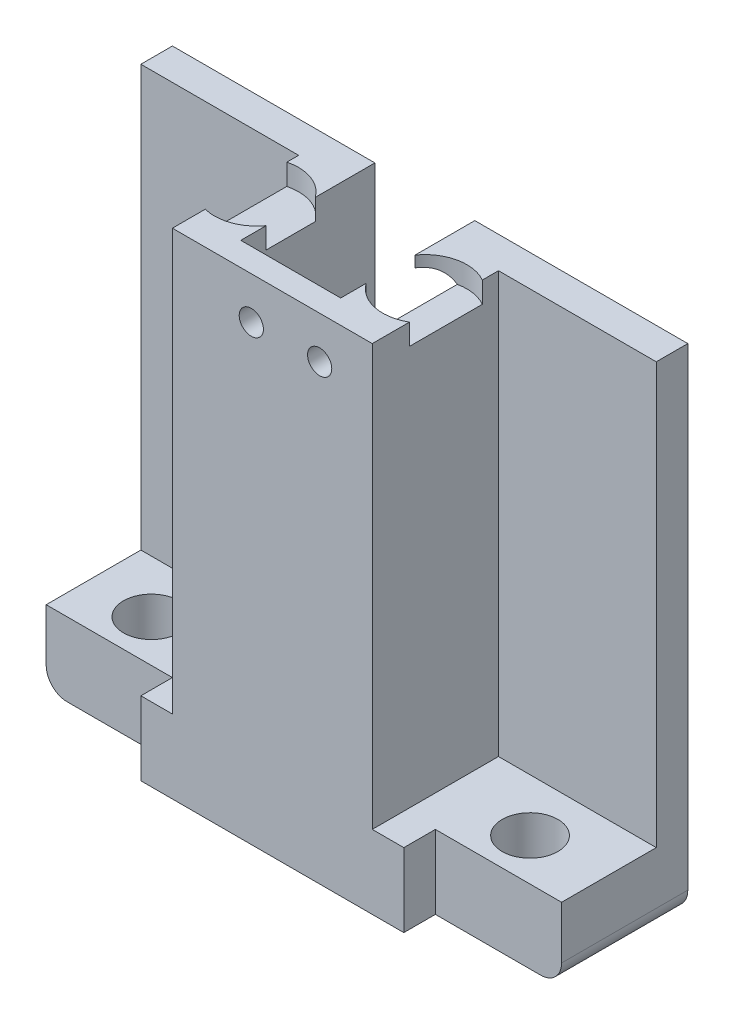
SolidWorks part; units mm, degrees
material "PLA"
ref_plane "前视基准面" through (0, 0, 0) normal (0, 0, 1) x (1, 0, 0)
ref_plane "上视基准面" through (0, 0, 0) normal (0, 1, 0) x (1, 0, 0)
ref_plane "右视基准面" through (0, 0, 0) normal (1, 0, 0) x (0, 0, -1)
other "Configuration Table"
sketch "草图1" plane through (0, 0, 0) normal (0, 0, 1) x (1, 0, 0)
  line L1 (-55, 53) -> (0, 53)
  line L2 (-55, 53) -> (-55, 0)
  line L3 (-55, 0) -> (0, 0)
  line L4 (0, 53) -> (0, 0)
  circle A2 centre (-52.5, 48) radius 1.15 construction
  circle A3 centre (-52.5, 41.5) radius 1.15 construction
  dimension "D2" = 53
  dimension "D4" = 2.5
  dimension "D7" = 2.3
  dimension "D8" = 6.5
  dimension "D9" = 5
  dimension "D10" = 52.5
  dimension "D3" = 55
extrude "凸台-拉伸1" add sketch "草图1" along normal blind 16
sketch "草图3" plane through (0, 0, 0) normal (0, -1, 0) x (1, 0, 0)
  line L0 (-55, 0) -> (0, 0) construction
  line L1 (0, 16) -> (0, 0) construction
  circle A0 centre (-43, 8) radius 2.65
  circle A1 centre (-7, 8) radius 2.65
  dimension "D1" = 36
  dimension "D2" = 5.3
  dimension "D3" = 8
  dimension "D4" = 7
extrude "切除-拉伸2" cut sketch "草图3" against normal through all
sketch "草图4" plane through (0, 0, 0) normal (0, -1, 0) x (1, 0, 0)
  line L0 (-29.75, 12.75) -> (-29.75, 0)
  line L2 (-29.75, 0) -> (-20.25, 0)
  line L3 (-20.25, 0) -> (-20.25, 12.75)
  line L4 (-25, 8) -> (-25, 23.0019) construction
  line L5 (-20.25, 12.75) -> (-29.75, 12.75)
  line L6 (-55, 0) -> (0, 0) construction
  line L7 (-7, 8) -> (-43, 8) construction
  circle A0 centre (-25, 8) radius 4.75 construction
  circle A1 centre (-7, 8) radius 2.65 construction
  circle A2 centre (-7, 8) radius 2.65 construction
  dimension "D1" = 9.5
  dimension "D2" = 9.5
extrude "切除-拉伸3" cut sketch "草图4" against normal through all
sketch "草图2" plane through (0, 0, 16) normal (0, 0, 1) x (1, 0, 0)
  line L0 (-37, 53) -> (-37, 0)
  line L1 (-12, 53) -> (-12, 0)
  line L2 (-37, 53) -> (-49, 53)
  line L3 (0, 53) -> (-55, 53) construction
  line L4 (0, 0) -> (0, 53)
  line L5 (0, 53) -> (-55, 53)
  line L6 (-55, 53) -> (-55, 0)
  line L7 (-55, 0) -> (0, 0)
  line L8 (0, 0) -> (0, 53)
  line L9 (0, 53) -> (-12, 53)
  line L12 (-49, 53) -> (-49, 0)
  line L13 (-49, 0) -> (-37, 0)
  line L14 (-49, 0) -> (-37, 0)
  line L15 (-12, 0) -> (0, 0)
  line M12 (0, 0) -> (0, 53)
  line M14 (0, 53) -> (-55, 53)
  line M31 (-55, 0) -> (0, 0)
  dimension "D2" = 37
  dimension "D3" = 12
  dimension "D4" = 12
  dimension "D1" = 0
extrude "切除-拉伸4" cut sketch "草图2" against normal blind 4 contours L12 L0 M14 M31 | L1 M14 M31 M12
sketch "草图5" plane through (0, 0, 12) normal (0, 0, 1) x (1, 0, 0)
  line L0 (-37, 53) -> (-37, 0) construction
  line L1 (-49, 53) -> (-37, 53)
  line L2 (-49, 53) -> (-49, 7)
  line L3 (-49, 7) -> (-37, 7)
  line L4 (-37, 53) -> (-37, 7)
  line L5 (0, 0) -> (0, 53) construction
  line L6 (-12, 53) -> (0, 53)
  line L7 (-12, 53) -> (-12, 7)
  line L8 (-12, 7) -> (0, 7)
  line L9 (0, 53) -> (0, 7)
  line L10 (-12, 53) -> (-12, 0) construction
  dimension "D1" = 46
extrude "切除-拉伸5" cut sketch "草图5" against normal blind 9
fillet "圆角1" radius 2 4 edges at (0, 53, 1.5) (-55, 53, 8) (0, 0, 6) (-55, 0, 8)
sketch "草图6" plane through (0, 0, 16) normal (0, 0, 1) x (1, 0, 0)
  line L0 (-49, 0) -> (-49, 53)
  line L1 (-53, 0) -> (-49, 0) construction
  line L2 (-49, 53) -> (-53, 53) construction
  line L3 (-53, 53) -> (-49, 53)
  line L4 (-49, 53) -> (-53, 53)
  line L5 (-55, 51) -> (-55, 2)
  line L6 (-53, 0) -> (-49, 0)
  line L7 (-49, 0) -> (-49, 53)
  line L9 (-55, 51) -> (-55, 2)
  line L12 (-49, 0) -> (-53, 0)
  line L13 (-37, 53) -> (-37, 0) construction
  arc A2 (-53, 53) -> (-55, 51) centre (-53, 51) ccw
  arc A3 (-55, 2) -> (-53, 0) centre (-53, 2) ccw
  arc A4 (-53, 53) -> (-55, 51) centre (-53, 51) ccw
  arc A5 (-55, 2) -> (-53, 0) centre (-53, 2) ccw
  dimension "D2" = 12
  dimension "D1" = 0
extrude "切除-拉伸6" cut sketch "草图6" against normal through all
fillet "圆角2" radius 2 2 edges at (-49, 53, 1.5) (-49, 0, 6)
sketch "草图12" plane through (0, 53, 0) normal (0, 1, 0) x (1, 0, 0)
  line L1 (-53.802, 11.0463) -> (2.1431, 11.0463)
  line L2 (-53.802, 11.0463) -> (-53.802, -22.1626)
  line L3 (-53.802, -22.1626) -> (2.1431, -22.1626)
  line L4 (2.1431, 11.0463) -> (2.1431, -22.1626)
  point P4 (2.1431, -22.1626)
extrude "切除-拉伸10" cut sketch "草图12" against normal blind 6
sketch "草图13" plane through (0, 0, 16) normal (0, 0, 1) x (1, 0, 0)
  line L0 (-12, 47) -> (-37, 47) construction
  line L1 (-49, 47) -> (-49, 7) construction
  circle A0 centre (-26.5, 43) radius 1.15
  circle A1 centre (-20, 43) radius 1.15
  point P8 (0, 0)
  dimension "D1" = 2.3
  dimension "D2" = 6.5
  dimension "D3" = 4
  dimension "D4" = 29
extrude "切除-拉伸11" cut sketch "草图13" against normal through all
sketch "草图8" [suppressed] plane through (0, 53, 0) normal (0, 1, 0) x (1, 0, 0)
  line L0 (-12, -16) -> (-37, -16) construction
  line L1 (-37, -16) -> (-27.65, -16)
  line L2 (-37, -16) -> (-37, -29)
  line L3 (-37, -29) -> (-27.65, -29)
  line L4 (-27.65, -16) -> (-27.65, -29)
  line L5 (-24.5, -16) -> (-24.5, -34.5504) construction
  line L6 (-21.35, -16) -> (-21.35, -29)
  line L7 (-12, -29) -> (-21.35, -29)
  line L8 (-12, -16) -> (-12, -29)
  line L9 (-12, -16) -> (-21.35, -16)
  dimension "D1" = 6.3
  dimension "D2" = 13
extrude "凸台-拉伸2" [suppressed] add sketch "草图8" against normal blind 6
sketch "草图9" [suppressed] plane through (-12, 0, 0) normal (1, 0, 0) x (0, 0, -1)
  line L0 (-16, 37) -> (-16, 0) construction
  line L1 (-29, 40) -> (-37.2325, 40) construction
  line L2 (-29, 37) -> (-29, 43) construction
  circle A0 centre (-16, 40) radius 1.15
  circle A1 centre (-22.5, 40) radius 1.15
  dimension "D1" = 2.3
  dimension "D2" = 0
  dimension "D3" = 6.5
extrude "切除-拉伸7" [suppressed] cut sketch "草图9" against normal through all
sketch "草图10" [suppressed] plane through (0, 43, 0) normal (0, 1, 0) x (1, 0, 0)
  line L0 (-19, -12.75) -> (-31, -12.75) construction
  line L1 (-27.65, -16) -> (-21.35, -16)
  line L2 (-27.65, -16) -> (-27.65, -12.75)
  line L3 (-27.65, -12.75) -> (-21.35, -12.75)
  line L4 (-21.35, -16) -> (-21.35, -12.75)
extrude "切除-拉伸8" [suppressed] cut sketch "草图10" against normal blind 7
sketch "草图11" plane through (0, 0, 16) normal (0, 0, 1) x (1, 0, 0)
  line L0 (-24.5, 57.8197) -> (-24.5, -14.2167) construction
  line L1 (-37, 53) -> (-34, 53)
  line L2 (-37, 53) -> (-37, 7)
  line L3 (-37, 7) -> (-34, 7)
  line L4 (-34, 53) -> (-34, 7)
  line L6 (-15, 53) -> (-15, 7)
  line L7 (-12, 7) -> (-15, 7)
  line L8 (-12, 53) -> (-12, 7)
  line L9 (-12, 53) -> (-15, 53)
  line L10 (-37, 0) -> (-12, 0) construction
  point P9 (-18.0887, 57.8197)
  point P14 (0, 0)
  point P16 (-24.5, 0)
  point P17 (0, 0)
  dimension "D1" = 3
extrude "切除-拉伸9" cut sketch "草图11" against normal up to surface (13 mm away) up to face at (-43, 27, 3)
sketch "草图14" plane through (0, 0, 16) normal (0, 0, 1) x (1, 0, 0)
  line L8 (-34, 47) -> (-34, 7)
  line L9 (-34, 7) -> (-37, 7)
  line L10 (-37, 7) -> (-37, 0)
  line L11 (-37, 0) -> (-12, 0)
  line L12 (-12, 0) -> (-12, 7)
  line L13 (-12, 7) -> (-15, 7)
  line L14 (-15, 7) -> (-15, 47)
  line L15 (-15, 47) -> (-34, 47)
  line L16 (-34, 47) -> (-34, 7)
  line L17 (-34, 7) -> (-37, 7)
  line L18 (-37, 7) -> (-37, 0)
  line L19 (-37, 0) -> (-12, 0)
  line L20 (-12, 0) -> (-12, 7)
  line L21 (-12, 7) -> (-15, 7)
  line L22 (-15, 7) -> (-15, 47)
  line L23 (-15, 47) -> (-34, 47)
  dimension "D1" = 0
extrude "切除-拉伸12" cut sketch "草图14" against normal blind 1
sketch "草图15" plane through (0, 0, 0) normal (0, 0, -1) x (-1, 0, 0)
  circle A0 centre (26.5, 43) radius 3
  circle A1 centre (20, 43) radius 2.95
  dimension "D1" = 6
  dimension "D2" = 5.9
extrude "切除-拉伸13" cut sketch "草图15" against normal up to surface (12.75 mm away) up to face at (-25.35, 43, 12.75)
sketch "草图16" plane through (0, 47, 0) normal (0, 1, 0) x (1, 0, 0)
  line L0 (-25, -12.75) -> (-25, 6.8254) construction
  line L1 (-20.25, -12.75) -> (-29.75, -12.75) construction
  line L2 (-15, -15) -> (-34, -15) construction
  circle A0 centre (-17, -8) radius 4
  circle A1 centre (-33, -8) radius 4
  dimension "D1" = 8
  dimension "D2" = 8
  dimension "D3" = 7
extrude "切除-拉伸14" cut sketch "草图16" against normal blind 2
